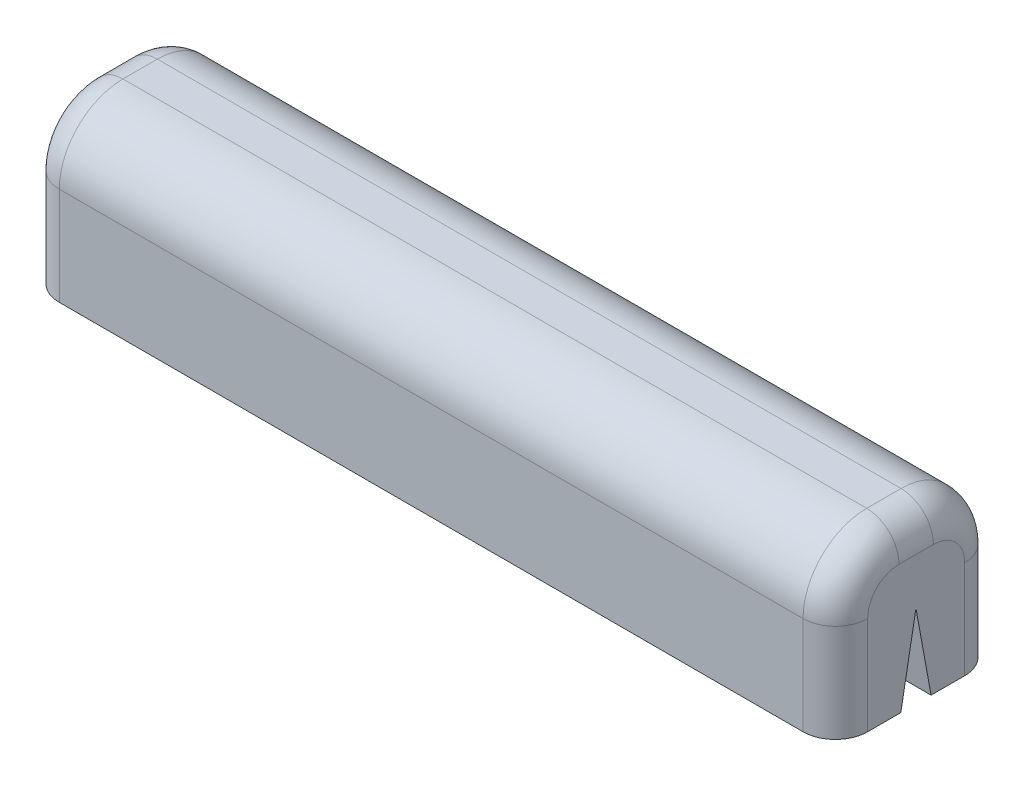
SolidWorks part; units mm, degrees
ref_plane "Front Plane" through (0, 0, 0) normal (0, 0, 1) x (1, 0, 0)
ref_plane "Top Plane" through (0, 0, 0) normal (0, 1, 0) x (1, 0, 0)
ref_plane "Right Plane" through (0, 0, 0) normal (1, 0, 0) x (0, 0, -1)
sketch "Sketch1" plane through (0, 0, 0) normal (1, 0, 0) x (0, 0, -1)
  line L1 (-4.7505, 0) -> (-2.3752, 12.9927)
  line L2 (-2.3752, 12.9927) -> (0, 0)
  line L7 (-15.0375, 0) -> (-15.0375, 25.4)
  line L8 (-15.0375, 25.4) -> (10.3625, 25.4)
  line L16 (-15.0375, 0) -> (-4.7505, 0)
  line L17 (0, 0) -> (10.3625, 0)
  line L18 (10.3625, 25.4) -> (10.3625, 0)
  dimension "D1" = 13.208
  dimension "D2" = 13.208
  dimension "D3" = 20.72
  dimension "D4" = 4.7505
  dimension "D5" = 10.287
  dimension "D6" = 25.4
  dimension "D7" = 25.4
extrude "Boss-Extrude1" add sketch "Sketch1" along normal blind 127 contours L7 L8 L18 L17 L2 L1 L16
fillet "Fillet3" radius 10 2 edges at (63.5, 25.4, 15.0375) (63.5, 25.4, -10.3625)
fillet "Fillet4" radius 5.08 10 edges at (0, 25.4, 2.3375) (127, 25.4, 2.3375) (0, 7.7, 15.0375) (0, 22.4711, 12.1085) (0, 7.7, -10.3625) (0, 22.4711, -7.4336) (127, 7.7, 15.0375) (127, 22.4711, 12.1085) (127, 7.7, -10.3625) (127, 22.4711, -7.4336)
